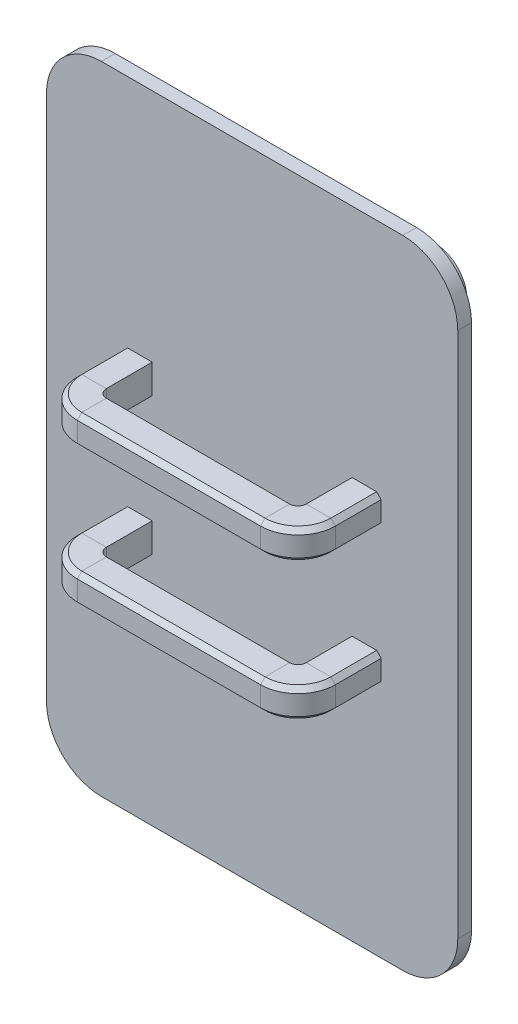
SolidWorks part; units mm, degrees
ref_plane "Front Plane" through (0, 0, 0) normal (0, 0, 1) x (1, 0, 0)
ref_plane "Top Plane" through (0, 0, 0) normal (0, 1, 0) x (1, 0, 0)
ref_plane "Right Plane" through (0, 0, 0) normal (1, 0, 0) x (0, 0, -1)
sketch "Sketch1" plane through (0, 0, 0) normal (0, 0, 1) x (1, 0, 0)
  line L0 (-131.5265, -25.8333) -> (-50.7265, -25.8333) construction
  line L1 (-131.5265, 39.1667) -> (-50.7265, 39.1667) construction
  line L2 (-131.5265, 39.1667) -> (-131.5265, -90.8333) construction
  line L3 (-131.5265, -90.8333) -> (-50.7265, -90.8333) construction
  line L4 (-50.7265, 39.1667) -> (-50.7265, -90.8333) construction
  line L5 (-91.1265, 39.1667) -> (-91.1265, -90.8333) construction
  line L6 (-131.0265, 38.6667) -> (-51.2265, 38.6667)
  line L7 (-51.2265, 38.6667) -> (-51.2265, -90.3333)
  line L8 (-131.0265, -90.3333) -> (-51.2265, -90.3333)
  line L9 (-131.0265, 38.6667) -> (-131.0265, -90.3333)
  line L13 (-131.5265, 39.1667) -> (-50.7265, 39.1667) construction
  line L16 (-50.7265, 39.1667) -> (-50.7265, -90.8333) construction
  dimension "D1" = 0.5
extrude "Boss-Extrude1" add sketch "Sketch1" along normal blind 4
fillet "Fillet1" radius 7 4 edges at (-51.2265, -90.3333, 2) (-131.0265, -90.3333, 2) (-131.0265, 38.6667, 2) (-51.2265, 38.6667, 2)
sketch "Sketch2" plane through (0, 0, 0) normal (0, 0, -1) x (-1, 0, 0)
  line L0 (51.2265, -25.8333) -> (131.0265, -25.8333)
  line L4 (51.2265, 31.6667) -> (51.2265, -83.3333)
  line L5 (58.2265, -90.3333) -> (124.0265, -90.3333)
  line L6 (131.0265, -83.3333) -> (131.0265, 31.6667)
  line L7 (124.0265, 38.6667) -> (58.2265, 38.6667)
  line L8 (51.2265, 31.6667) -> (51.2265, -83.3333)
  line L9 (58.2265, -90.3333) -> (124.0265, -90.3333)
  line L10 (131.0265, -83.3333) -> (131.0265, 31.6667)
  line L11 (124.0265, 38.6667) -> (58.2265, 38.6667)
  circle A0 centre (91.1265, -85.8333) radius 3.325 construction
  circle A1 centre (126.5265, -56.5833) radius 3.325 construction
  circle A2 centre (126.5265, 1.9167) radius 3.325 construction
  circle A3 centre (55.7265, -56.5833) radius 3.325 construction
  arc A4 (51.2265, -83.3333) -> (58.2265, -90.3333) centre (58.2265, -83.3333) ccw
  arc A5 (124.0265, -90.3333) -> (131.0265, -83.3333) centre (124.0265, -83.3333) ccw
  arc A6 (131.0265, 31.6667) -> (124.0265, 38.6667) centre (124.0265, 31.6667) ccw
  arc A7 (58.2265, 38.6667) -> (51.2265, 31.6667) centre (58.2265, 31.6667) ccw
  arc A8 (51.2265, -83.3333) -> (58.2265, -90.3333) centre (58.2265, -83.3333) ccw
  arc A9 (124.0265, -90.3333) -> (131.0265, -83.3333) centre (124.0265, -83.3333) ccw
  arc A10 (131.0265, 31.6667) -> (124.0265, 38.6667) centre (124.0265, 31.6667) ccw
  arc A11 (58.2265, 38.6667) -> (51.2265, 31.6667) centre (58.2265, 31.6667) ccw
  circle A12 centre (55.7265, 1.9167) radius 3.325 construction
  circle A13 centre (91.1265, -85.8333) radius 3.325
  circle A14 centre (126.5265, -56.5833) radius 3.325
  circle A15 centre (126.5265, 1.9167) radius 3.325
  circle A16 centre (55.7265, -56.5833) radius 3.325
  circle A17 centre (55.7265, 1.9167) radius 3.325
  circle A18 centre (91.1265, 34.1667) radius 3.325
  dimension "D1" = 0
extrude "Cut-Extrude2" cut sketch "Sketch2" against normal blind 3.2 contours A17 | A18 | A16 | A13 | A15 | A14
sketch "Sketch3" plane through (0, 0, 4) normal (0, 0, 1) x (1, 0, 0)
  line L0 (-124.0265, -95.3333) -> (-58.2265, -95.3333)
  line L1 (-46.2265, -83.3333) -> (-46.2265, 31.6667)
  line L2 (-58.2265, 43.6667) -> (-124.0265, 43.6667)
  line L3 (-136.0265, 31.6667) -> (-136.0265, -83.3333)
  line L4 (-124.0265, -90.3333) -> (-58.2265, -90.3333)
  line L5 (-51.2265, -83.3333) -> (-51.2265, 31.6667)
  line L6 (-58.2265, 38.6667) -> (-124.0265, 38.6667)
  line L7 (-131.0265, 31.6667) -> (-131.0265, -83.3333)
  line L8 (-124.0265, -90.3333) -> (-58.2265, -90.3333)
  line L9 (-51.2265, -83.3333) -> (-51.2265, 31.6667)
  line L10 (-58.2265, 38.6667) -> (-124.0265, 38.6667)
  line L11 (-131.0265, 31.6667) -> (-131.0265, -83.3333)
  arc A0 (-58.2265, -95.3333) -> (-46.2265, -83.3333) centre (-58.2265, -83.3333) ccw
  arc A1 (-46.2265, 31.6667) -> (-58.2265, 43.6667) centre (-58.2265, 31.6667) ccw
  arc A2 (-124.0265, 43.6667) -> (-136.0265, 31.6667) centre (-124.0265, 31.6667) ccw
  arc A3 (-136.0265, -83.3333) -> (-124.0265, -95.3333) centre (-124.0265, -83.3333) ccw
  arc A4 (-58.2265, -90.3333) -> (-51.2265, -83.3333) centre (-58.2265, -83.3333) ccw
  arc A5 (-51.2265, 31.6667) -> (-58.2265, 38.6667) centre (-58.2265, 31.6667) ccw
  arc A6 (-124.0265, 38.6667) -> (-131.0265, 31.6667) centre (-124.0265, 31.6667) ccw
  arc A7 (-131.0265, -83.3333) -> (-124.0265, -90.3333) centre (-124.0265, -83.3333) ccw
  arc A8 (-58.2265, -90.3333) -> (-51.2265, -83.3333) centre (-58.2265, -83.3333) ccw
  arc A9 (-51.2265, 31.6667) -> (-58.2265, 38.6667) centre (-58.2265, 31.6667) ccw
  arc A10 (-124.0265, 38.6667) -> (-131.0265, 31.6667) centre (-124.0265, 31.6667) ccw
  arc A11 (-131.0265, -83.3333) -> (-124.0265, -90.3333) centre (-124.0265, -83.3333) ccw
  line M9 (-124.0265, -90.3333) -> (-58.2265, -90.3333)
  arc M10 (-58.2265, -90.3333) -> (-51.2265, -83.3333) centre (-58.2265, -83.3333) ccw
  line M11 (-51.2265, -83.3333) -> (-51.2265, 31.6667)
  arc M12 (-51.2265, 31.6667) -> (-58.2265, 38.6667) centre (-58.2265, 31.6667) ccw
  line M13 (-58.2265, 38.6667) -> (-124.0265, 38.6667)
  arc M14 (-124.0265, 38.6667) -> (-131.0265, 31.6667) centre (-124.0265, 31.6667) ccw
  line M15 (-131.0265, 31.6667) -> (-131.0265, -83.3333)
  arc M16 (-131.0265, -83.3333) -> (-124.0265, -90.3333) centre (-124.0265, -83.3333) ccw
  dimension "D1" = 0
  dimension "D2" = 5
extrude "Boss-Extrude3" add sketch "Sketch3" along normal blind 3 contours M16 M9 M10 M11 M12 M13 M14 M15 | L3 A3 L0 A0 L1 A1 L2 A2 M9 M16 M15 M14 M13 M12 M11 M10 | L8 A8 L9 A9 L10 A10 L11 A11
sketch "Sketch6" plane through (0, 0, 7) normal (0, 0, 1) x (1, 0, 0)
  line L0 (-91.1265, 43.6667) -> (-91.1265, -95.3333) construction
  line L1 (-58.2265, 43.6667) -> (-124.0265, 43.6667) construction
  line L2 (-124.0265, -95.3333) -> (-58.2265, -95.3333) construction
  line L3 (-136.0265, -25.8333) -> (-46.2265, -25.8333) construction
  line L4 (-136.0265, 31.6667) -> (-136.0265, -83.3333) construction
  line L5 (-46.2265, -83.3333) -> (-46.2265, 31.6667) construction
  line L6 (-62.9515, -14.0083) -> (-62.9515, -7.6583)
  line L7 (-116.1265, -40.8333) -> (-66.1265, -40.8333) construction
  line L8 (-116.1265, -40.8333) -> (-116.1265, -10.8333) construction
  line L9 (-116.1265, -10.8333) -> (-66.1265, -10.8333) construction
  line L10 (-66.1265, -40.8333) -> (-66.1265, -10.8333) construction
  line L11 (-116.1265, -40.8333) -> (-66.1265, -10.8333) construction
  line L12 (-116.1265, -10.8333) -> (-66.1265, -40.8333) construction
  line L13 (-119.3015, -14.0083) -> (-112.9515, -14.0083)
  line L14 (-119.3015, -14.0083) -> (-119.3015, -7.6583)
  line L15 (-119.3015, -7.6583) -> (-112.9515, -7.6583)
  line L16 (-112.9515, -14.0083) -> (-112.9515, -7.6583)
  line L17 (-119.3015, -14.0083) -> (-112.9515, -7.6583) construction
  line L18 (-119.3015, -7.6583) -> (-112.9515, -14.0083) construction
  line L19 (-62.9515, -14.0083) -> (-69.3015, -14.0083)
  line L20 (-69.3015, -14.0083) -> (-69.3015, -7.6583)
  line L21 (-62.9515, -7.6583) -> (-69.3015, -7.6583)
  line L22 (-119.3015, -37.6583) -> (-119.3015, -44.0083)
  line L23 (-119.3015, -37.6583) -> (-112.9515, -37.6583)
  line L24 (-112.9515, -37.6583) -> (-112.9515, -44.0083)
  line L25 (-69.3015, -37.6583) -> (-69.3015, -44.0083)
  line L26 (-62.9515, -37.6583) -> (-69.3015, -37.6583)
  line L27 (-62.9515, -37.6583) -> (-62.9515, -44.0083)
  line L28 (-62.9515, -44.0083) -> (-69.3015, -44.0083)
  line L29 (-119.3015, -44.0083) -> (-112.9515, -44.0083)
  circle A0 centre (-116.1265, -10.8333) radius 3.175 construction
  circle A1 centre (-66.1265, -10.8333) radius 3.175 construction
  circle A2 centre (-66.1265, -40.8333) radius 3.175 construction
  circle A3 centre (-116.1265, -40.8333) radius 3.175 construction
  point P12 (-91.1265, -25.8333)
  dimension "D3" = 6.35
  dimension "D1" = 30
  dimension "D2" = 50
sketch3d "3DSketch3"
  line L0 (-116.1265, -10.8333, 7) -> (-116.1265, -10.8333, 17)
  line L2 (-116.1265, -10.8333, 22) -> (-116.1265, -10.8333, 7)
  line L3 (-111.1265, -10.8333, 22) -> (-71.1265, -10.8333, 22)
  line L4 (-66.1265, -10.8333, 17) -> (-66.1265, -10.8333, 7)
  line L5 (-116.1265, -10.8333, 7) -> (-66.1265, -10.8333, 7)
  line L6 (-116.1265, -40.8333, 7) -> (-116.1265, -40.8333, 17)
  line L8 (-116.1265, -40.8333, 27) -> (-116.1265, -40.8333, 7)
  line L9 (-106.1265, -40.8333, 27) -> (-76.1265, -40.8333, 27)
  line L10 (-66.1265, -40.8333, 17) -> (-66.1265, -40.8333, 7)
  line L11 (-116.1265, -40.8333, 7) -> (-66.1265, -40.8333, 7)
  arc A0 (-66.1265, -10.8333, 17) -> (-71.1265, -10.8333, 22) centre (-71.1265, -10.8333, 17) ccw
  arc A1 (-116.1265, -10.8333, 17) -> (-111.1265, -10.8333, 22) centre (-111.1265, -10.8333, 17) ccw
  arc A2 (-66.1265, -40.8333, 17) -> (-76.1265, -40.8333, 27) centre (-76.1265, -40.8333, 17) ccw
  arc A3 (-106.1265, -40.8333, 27) -> (-116.1265, -40.8333, 17) centre (-106.1265, -40.8333, 17) ccw
  point P8 (-66.1265, -10.8333, 22)
  point P9 (-71.1265, -15.8333, 17)
  point P12 (-116.1265, -10.8333, 22)
  point P14 (-111.1265, -5.8333, 17)
  point P23 (-66.1265, -40.8333, 27)
  point P24 (-76.1265, -50.8333, 17)
  point P27 (-116.1265, -40.8333, 27)
  point P29 (-106.1265, -50.8333, 17)
  dimension "D2" = 5
  dimension "D4" = 10
  dimension "D1" = 15
  dimension "D3" = 20
sweep "Sweep1" add profiles "Sketch6" path "3DSketch3"
chamfer "Chamfer1" distance 1 angle 45 10 edges at (-62.9515, -14.0083, 12) (-65.3459, -14.0083, 22.7806) (-91.1265, -14.0083, 25.175) (-116.9071, -14.0083, 22.7806) (-119.3015, -14.0083, 12) (-62.9515, -7.6583, 12) (-65.3459, -7.6583, 22.7806) (-91.1265, -7.6583, 25.175) (-116.9071, -7.6583, 22.7806) (-119.3015, -7.6583, 12)
ref_plane "Plane1" through (0, -25.8333, 0) normal (0, 1, 0) x (1, 0, 0)
mirror "Mirror1" about plane through (0, -25.8333, 0) normal (0, 1, 0) of "Chamfer1", "Sweep1"
